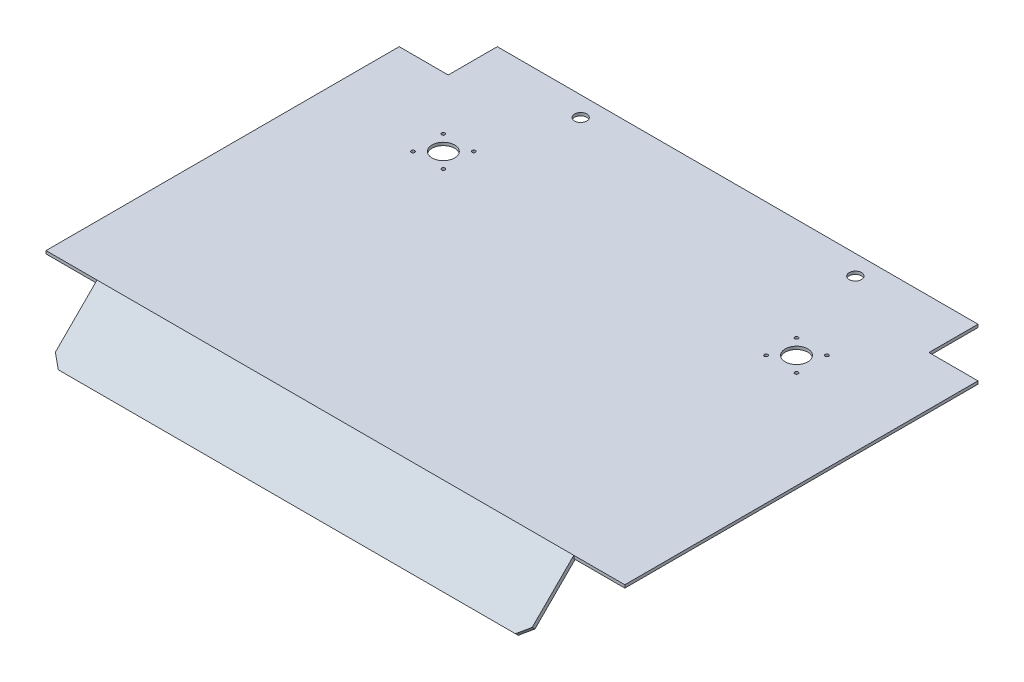
SolidWorks part; units mm, degrees
ref_plane "Front Plane" through (0, 0, 0) normal (0, 0, 1) x (1, 0, 0)
ref_plane "Top Plane" through (0, 0, 0) normal (0, 1, 0) x (1, 0, 0)
ref_plane "Right Plane" through (0, 0, 0) normal (1, 0, 0) x (0, 0, -1)
sketch "Sketch1" plane through (0, 0, 0) normal (0, 1, 0) x (1, 0, 0)
  line L0 (-221.6278, -114.5156) -> (-221.6278, 245.4844)
  line L1 (-221.6278, 245.4844) -> (-171.6278, 245.4844)
  line L2 (-171.6278, 245.4844) -> (-171.6278, 295.4844)
  line L3 (-171.6278, 295.4844) -> (318.3722, 295.4844)
  line L4 (318.3722, 295.4844) -> (318.3722, 245.4844)
  line L5 (318.3722, 245.4844) -> (368.3722, 245.4844)
  line L6 (368.3722, 245.4844) -> (368.3722, -114.5156)
  line L7 (368.3722, -114.5156) -> (-221.6278, -114.5156)
  line L8 (-106.6278, 175.4844) -> (253.3722, 175.4844) construction
  line L9 (-171.6278, 275.4844) -> (318.3722, 275.4844) construction
  line L10 (-127.8778, 196.7344) -> (-85.3778, 154.2344) construction
  line L15 (-127.3554, 154.7568) -> (-85.3778, 196.7344) construction
  line L16 (-122.1278, 190.9844) -> (-122.1278, 159.9844) construction
  line L17 (-122.1278, 159.9844) -> (-91.1278, 159.9844) construction
  line L18 (-91.1278, 159.9844) -> (-91.1278, 190.9844) construction
  line L19 (-91.1278, 190.9844) -> (-122.1278, 190.9844) construction
  line L20 (237.8722, 190.9844) -> (268.8722, 190.9844) construction
  line L21 (237.8722, 159.9844) -> (237.8722, 190.9844) construction
  line L22 (268.8722, 159.9844) -> (237.8722, 159.9844) construction
  line L23 (268.8722, 190.9844) -> (268.8722, 159.9844) construction
  line L24 (274.6222, 154.2344) -> (232.1222, 196.7344) construction
  line L25 (274.6222, 196.7344) -> (232.1222, 154.2344) construction
  line L26 (318.3722, 245.4844) -> (318.3722, -2.3669) construction
  circle A0 centre (-106.6278, 175.4844) radius 11.5
  circle A1 centre (-122.1278, 190.9844) radius 1.75
  circle A2 centre (-91.1278, 190.9844) radius 1.75
  circle A3 centre (-91.1278, 159.9844) radius 1.75
  circle A4 centre (-122.1278, 159.9844) radius 1.75
  circle A5 centre (268.8722, 159.9844) radius 1.75
  circle A6 centre (237.8722, 159.9844) radius 1.75
  circle A7 centre (237.8722, 190.9844) radius 1.75
  circle A8 centre (268.8722, 190.9844) radius 1.75
  circle A9 centre (253.3722, 175.4844) radius 11.5
  circle A10 centre (-66.6278, 275.4844) radius 6.25
  circle A11 centre (213.3722, 275.4844) radius 6.25
  point P2 (73.3722, 295.4844)
  dimension "D9" = 3.5
  dimension "D14" = 280
  dimension "D16" = 12.5
  dimension "D17" = 12.5
  dimension "D1" = 50
  dimension "D2" = 50
  dimension "D3" = 50
  dimension "D4" = 50
  dimension "D5" = 590
  dimension "D6" = 360
  dimension "D7" = 42.5
  dimension "D8" = 42.5
  dimension "D10" = 31
  dimension "D11" = 360
  dimension "D12" = 180
  dimension "D13" = 70
  dimension "D15" = 140
  dimension "D18" = 100
extrude "Boss-Extrude1" add sketch "Sketch1" along normal blind 3
ref_plane "Plane1" through (0, 58.7578, 58.7578) normal (0, 0.7071, 0.7071) x (1, 0, 0)
sketch "Sketch2" plane through (0, 58.7578, 58.7578) normal (0, 0.7071, 0.7071) x (1, 0, 0)
  line L0 (-221.6278, -78.8534) -> (368.3722, -78.8534) construction
  line L1 (-169.6278, -78.8534) -> (316.3722, -78.8534)
  line L2 (-169.6278, -78.8534) -> (-169.6278, -148.8534)
  line L3 (-169.6278, -148.8534) -> (316.3722, -148.8534)
  line L4 (316.3722, -78.8534) -> (316.3722, -148.8534)
  dimension "D1" = 52
  dimension "D2" = 52
  dimension "D3" = 70
extrude "Boss-Extrude2" add sketch "Sketch2" against normal blind 4
chamfer "Chamfer1" distance 10 angle 45 2 edges at (-169.6278, -47.9117, 162.5988) (316.3722, -47.9117, 162.5988)
